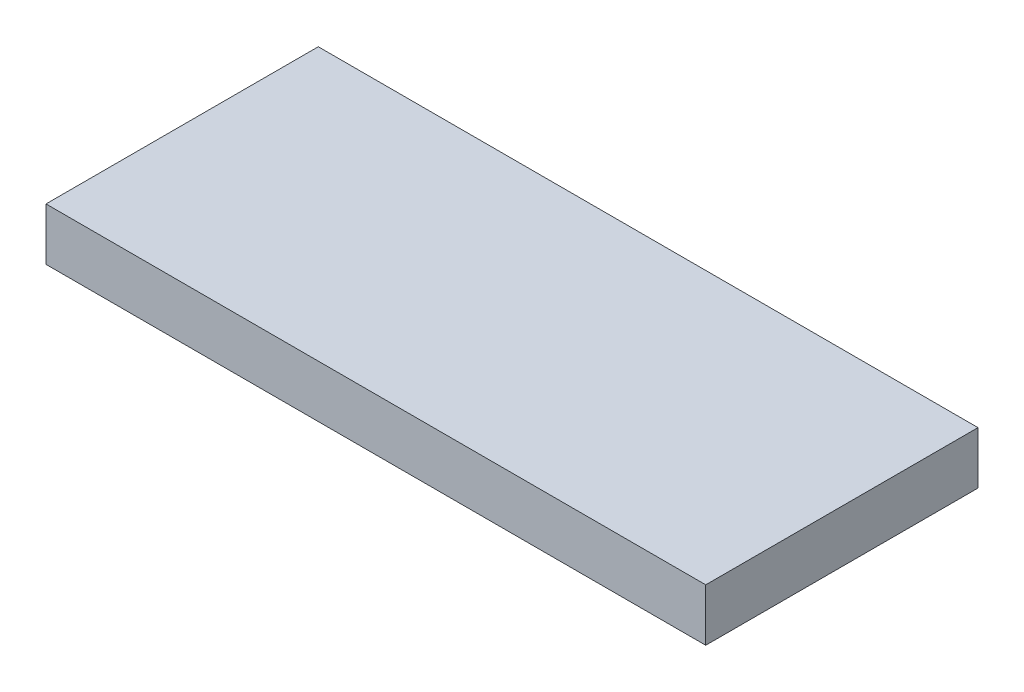
SolidWorks part; units mm, degrees
ref_plane "Front Plane" through (0, 0, 0) normal (0, 0, 1) x (1, 0, 0)
ref_plane "Top Plane" through (0, 0, 0) normal (0, 1, 0) x (1, 0, 0)
ref_plane "Right Plane" through (0, 0, 0) normal (1, 0, 0) x (0, 0, -1)
sketch "Sketch1" plane through (0, 0, 0) normal (0, 1, 0) x (1, 0, 0)
  line L1 (0, 0) -> (63, 0)
  line L2 (0, 0) -> (0, 26)
  line L3 (0, 26) -> (63, 26)
  line L4 (63, 0) -> (63, 26)
  dimension "D1" = 26
  dimension "D2" = 63
extrude "Boss-Extrude1" add sketch "Sketch1" along normal blind 5
sketch "Sketch2" plane through (0, 5, 0) normal (0, 1, 0) x (1, 0, 0)
  line L1 (0, 26) -> (10, 26)
  line L2 (0, 26) -> (0, 20)
  line L3 (0, 20) -> (10, 20)
  line L4 (10, 26) -> (10, 20)
  line L5 (63, 26) -> (53, 26)
  line L6 (63, 26) -> (63, 20)
  line L7 (63, 20) -> (53, 20)
  line L8 (53, 26) -> (53, 20)
  line L9 (63, 0) -> (53, 0)
  line L10 (63, 0) -> (63, 6)
  line L11 (63, 6) -> (53, 6)
  line L12 (53, 0) -> (53, 6)
  line L13 (0, 0) -> (10, 0)
  line L14 (0, 0) -> (0, 6)
  line L15 (0, 6) -> (10, 6)
  line L16 (10, 0) -> (10, 6)
  dimension "D1" = 10
  dimension "D2" = 6
